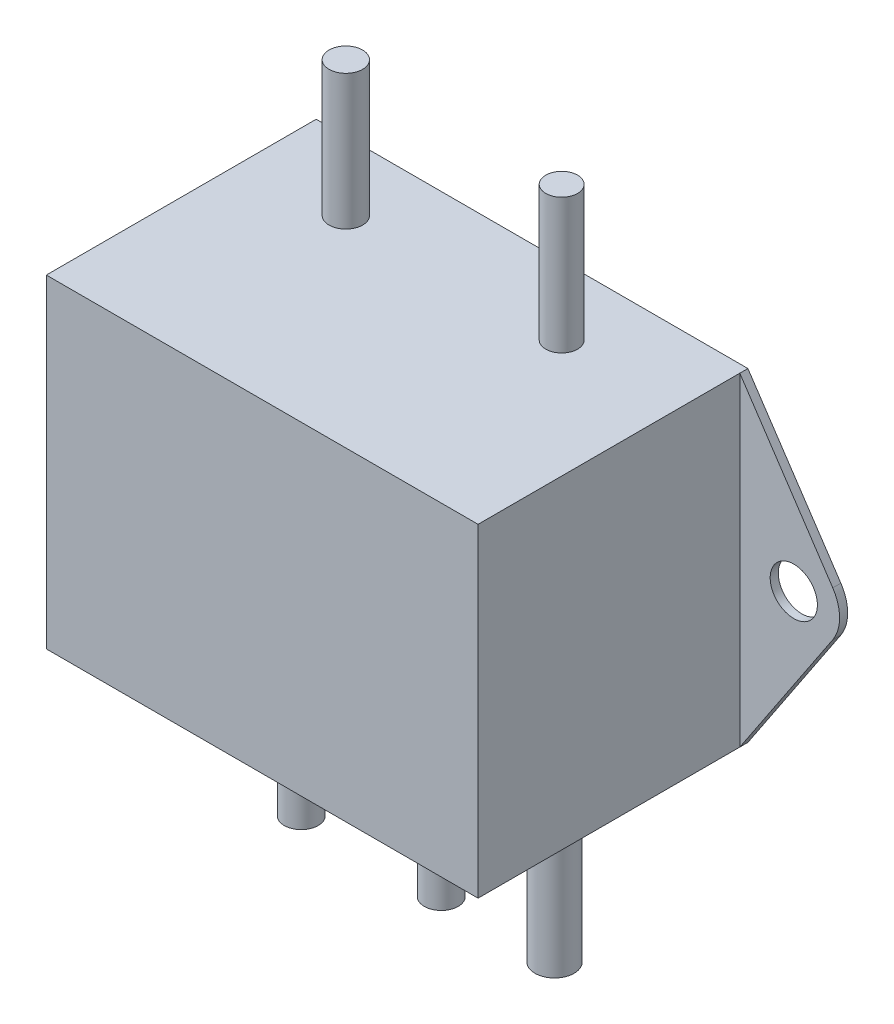
SolidWorks part; units mm, degrees
ref_plane "前视基准面" through (0, 0, 0) normal (0, 0, 1) x (1, 0, 0)
ref_plane "上视基准面" through (0, 0, 0) normal (0, 1, 0) x (1, 0, 0)
ref_plane "右视基准面" through (0, 0, 0) normal (1, 0, 0) x (0, 0, -1)
sketch "草图1" plane through (0, 0, 0) normal (0, 0, 1) x (1, 0, 0)
  line L0 (0, 2.3089) -> (0, 30.0156) construction
  line L1 (-16, 12) -> (16, 12)
  line L2 (-16, 12) -> (-16, -12)
  line L3 (-16, -12) -> (16, -12)
  line L4 (16, 12) -> (16, -12)
  line L5 (0, 0) -> (46.9184, 0) construction
  dimension "D1" = 32
  dimension "D2" = 24
extrude "凸台-拉伸1" add sketch "草图1" along normal blind 20
sketch "草图2" plane through (0, 0, 0) normal (0, 0, 1) x (1, 0, 0)
  line L0 (-16, 12) -> (-24, 0)
  line L1 (-24, 0) -> (-16, -12)
  line L2 (-16, -12) -> (-16, 12)
  line L3 (0, 0) -> (0, 15.3509) construction
  line L4 (16, -12) -> (16, 12)
  line L5 (24, 0) -> (16, -12)
  line L6 (16, 12) -> (24, 0)
  dimension "D1" = 48
extrude "凸台-拉伸2" add sketch "草图2" along normal blind 0.6
sketch "草图3" plane through (0, 0, 0.6) normal (0, 0, 1) x (1, 0, 0)
  line L0 (0, 0) -> (0, 13.3232) construction
  circle A0 centre (-20, 0) radius 1.75
  circle A1 centre (20, 0) radius 1.75
  dimension "D2" = 3.5
  dimension "D1" = 40
extrude "切除-拉伸1" cut sketch "草图3" against normal through all
fillet "圆角1" radius 3 2 edges at (24, 0, 0.3) (-24, 0, 0.3)
sketch "草图4" plane through (0, 12, 0) normal (0, 1, 0) x (1, 0, 0)
  circle A0 centre (-8.7256, -5.0753) radius 1.242
  circle A1 centre (7.2713, -5.0753) radius 1.1769
extrude "凸台-拉伸3" add sketch "草图4" along normal blind 10
sketch "草图5" plane through (0, -12, 0) normal (0, -1, 0) x (1, 0, 0)
  circle A0 centre (-10.8408, 6.2652) radius 1.256
  circle A1 centre (-0.4627, 6.2652) radius 1.256
  circle A2 centre (7.9323, 6.2652) radius 1.4497
extrude "凸台-拉伸4" add sketch "草图5" along normal blind 15
